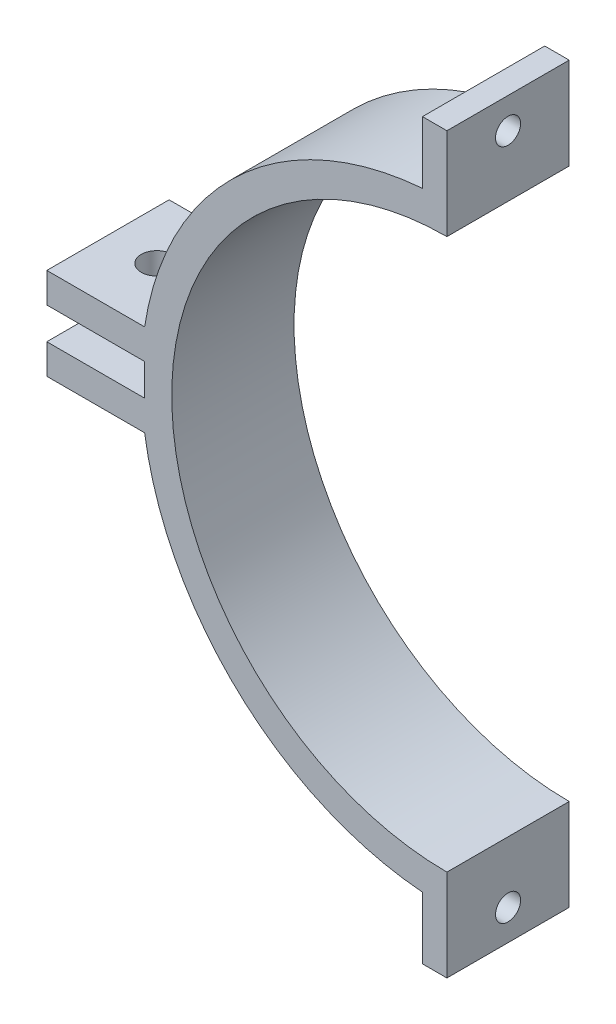
SolidWorks part; units mm, degrees
ref_plane "Front Plane" through (0, 0, 0) normal (0, 0, 1) x (1, 0, 0)
ref_plane "Top Plane" through (0, 0, 0) normal (0, 1, 0) x (1, 0, 0)
ref_plane "Right Plane" through (0, 0, 0) normal (1, 0, 0) x (0, 0, -1)
sketch "Sketch1" plane through (0, 0, 0) normal (0, 0, 1) x (1, 0, 0)
  line L0 (0, 45) -> (0, 60)
  line L1 (0, 60) -> (-4, 60)
  line L2 (-4, 60) -> (-4, 49.8397)
  line L3 (-50, 0) -> (-50, 38.0253) construction
  line L4 (0, 0) -> (65.2972, 0) construction
  line L5 (-49.4343, -7.5) -> (-65.4343, -7.5)
  line L6 (-49.4343, -7.5) -> (-49.4343, 7.5)
  line L7 (-49.4343, 7.5) -> (-65.4343, 7.5)
  line L8 (-65.4343, -7.5) -> (-65.4343, 7.5)
  line L9 (-49.4343, -7.5) -> (-65.4343, 7.5) construction
  line L10 (-49.4343, 7.5) -> (-65.4343, -7.5) construction
  line L11 (0, -45) -> (0, -60)
  line L12 (0, -60) -> (-4, -60)
  line L13 (-4, -60) -> (-4, -49.8397)
  arc A0 (0, 45) -> (0, -45) centre (0, 0) ccw
  arc A1 (0, 50) -> (0, -50) centre (0, 0) ccw
  point P10 (-57.4343, 0)
  dimension "D1" = 45
  dimension "D2" = 50
  dimension "D3" = 4
  dimension "D4" = 15
  dimension "D5" = 16
  dimension "D6" = 15
extrude "Boss-Extrude1" add sketch "Sketch1" along normal blind 20 contours A1 L7 L8 L5 | L0 A1 L6 L11 A0 | A1 L0 L1 L2 | A1 L13 L12 L11
sketch "Sketch2" plane through (-4, 0, 0) normal (-1, 0, 0) x (0, 0, 1)
  line L1 (20, 60) -> (0, 60) construction
  line L4 (0, 60) -> (0, 49.8397) construction
  circle A0 centre (10, 55) radius 2.05
  dimension "D1" = 4.1
  dimension "D2" = 5
  dimension "D3" = 10
extrude "Cut-Extrude1" cut sketch "Sketch2" against normal up to next
mirror "Mirror1" about plane through (0, 0, 0) normal (0, 1, 0) of "Cut-Extrude1"
sketch "Sketch3" plane through (-65.4343, 0, 0) normal (-1, 0, 0) x (0, 0, 1)
  line L0 (0, 0) -> (20, 0) construction
  line L1 (0, -7.5) -> (0, 7.5) construction
  line L2 (20, -7.5) -> (20, 7.5) construction
  line L3 (0, 2.6) -> (20, 2.6)
  line L4 (0, -7.5) -> (20, -7.5)
  line L5 (0, -7.5) -> (0, 7.5)
  line L6 (0, 7.5) -> (20, 7.5)
  line L7 (20, -7.5) -> (20, 7.5)
  line L8 (0, -7.5) -> (20, 7.5) construction
  line L9 (0, 7.5) -> (20, -7.5) construction
  line L10 (0, -2.6) -> (20, -2.6)
  point P6 (10, 0)
  point P7 (10, 0)
  line M7 (0, 7.5) -> (0, -7.5)
  dimension "D1" = 4.9
extrude "Cut-Extrude2" cut sketch "Sketch3" against normal blind 16 contours L10 L7 L3 M7
sketch "Sketch4" plane through (0, 7.5, 0) normal (0, 1, 0) x (1, 0, 0)
  line L1 (-49.4343, 0) -> (-65.4343, -20) construction
  line L2 (-65.4343, 0) -> (-49.4343, -20) construction
  circle A0 centre (-57.4343, -10) radius 2.55
  dimension "D1" = 5.1
extrude "Cut-Extrude3" cut sketch "Sketch4" against normal through all
